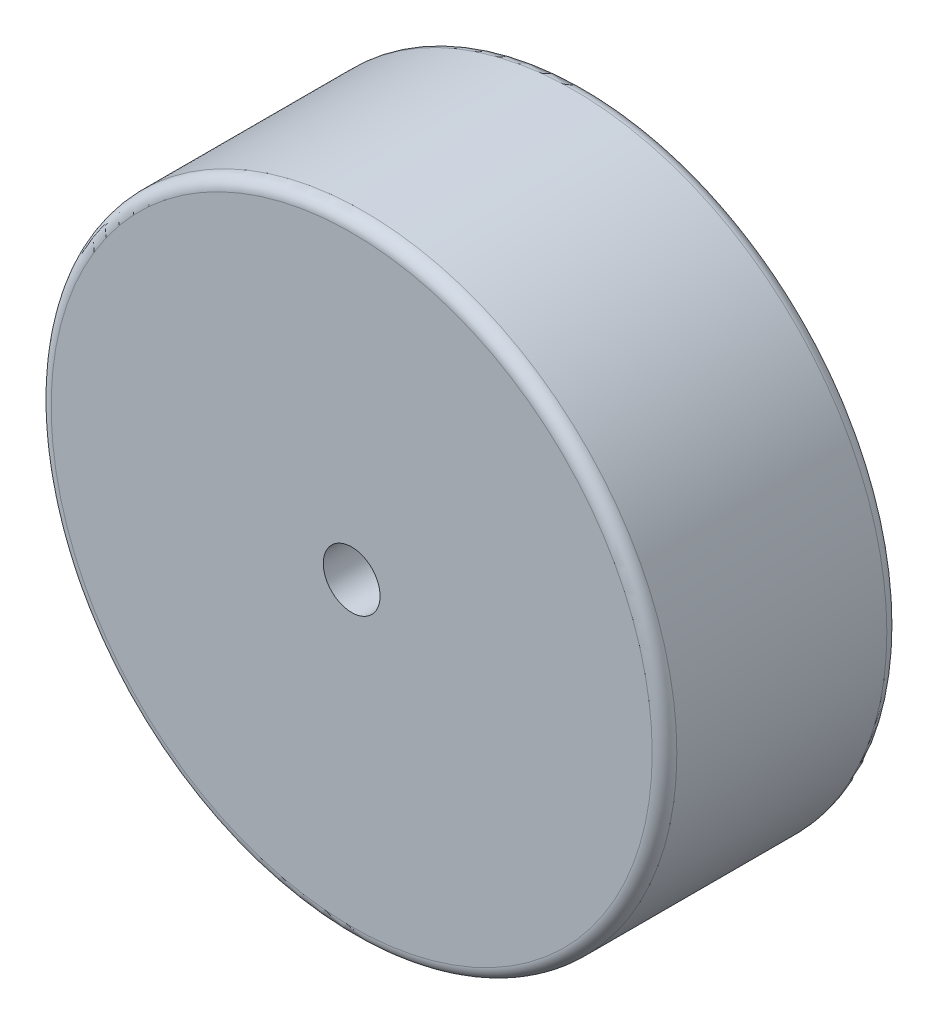
SolidWorks part; units mm, degrees
ref_plane "Front Plane" through (0, 0, 0) normal (0, 0, 1) x (1, 0, 0)
ref_plane "Top Plane" through (0, 0, 0) normal (0, 1, 0) x (1, 0, 0)
ref_plane "Right Plane" through (0, 0, 0) normal (1, 0, 0) x (0, 0, -1)
sketch "body sketch" plane through (0, 0, 0) normal (0, 0, 1) x (1, 0, 0)
  circle A0 centre (0, 0) radius 25.4
  dimension "D1" = 50.8
extrude "wheel body" add sketch "body sketch" along normal mid plane 19.05 contours A0
sketch "hole sketch" plane through (0, 0, 9.525) normal (0, 0, 1) x (1, 0, 0)
  circle A0 centre (0, 0) radius 2.305
  dimension "D1" = 4.61
fillet "fillet wheel" radius 1 2 edges at (25.4, 0, -9.525) (25.4, 0, 9.525)
extrude "hole shaft" cut sketch "hole sketch" against normal blind 15 contours A0
